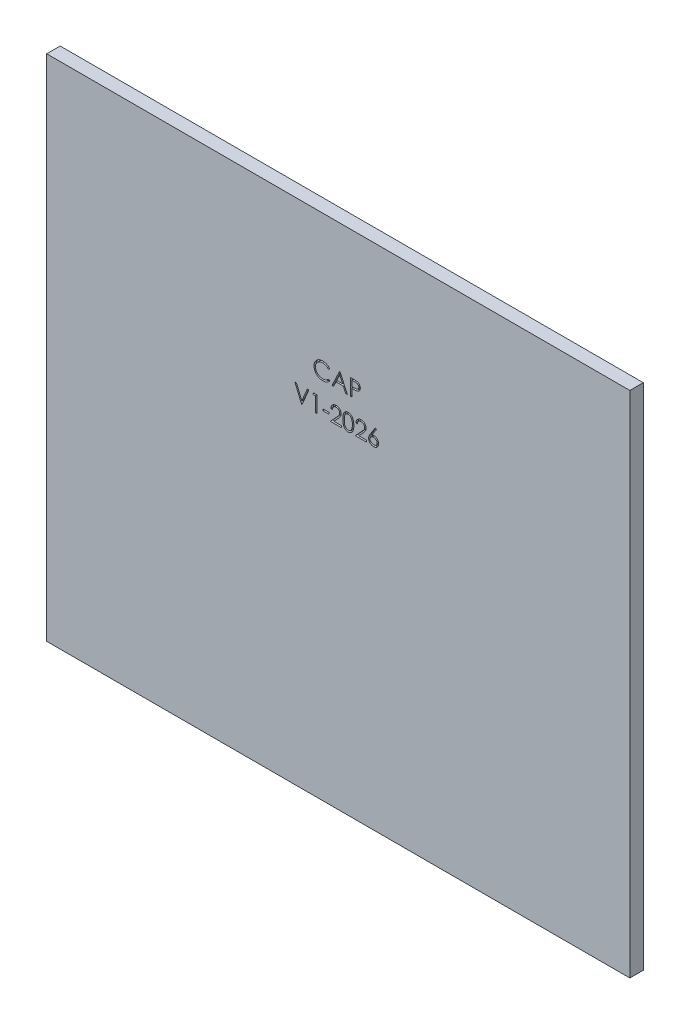
SolidWorks part; units mm, degrees
ref_plane "Plan de face" through (0, 0, 0) normal (0, 0, 1) x (1, 0, 0)
ref_plane "Plan de dessus" through (0, 0, 0) normal (0, 1, 0) x (1, 0, 0)
ref_plane "Plan de droite" through (0, 0, 0) normal (1, 0, 0) x (0, 0, -1)
sketch "Esquisse1" plane through (0, 0, 0) normal (0, 0, 1) x (1, 0, 0)
  line L1 (-62.8, -54.8) -> (62.8, -54.8)
  line L2 (-62.8, -54.8) -> (-62.8, 54.8)
  line L3 (-62.8, 54.8) -> (62.8, 54.8)
  line L4 (62.8, -54.8) -> (62.8, 54.8)
  line L5 (-62.8, -54.8) -> (62.8, 54.8) construction
  line L6 (-62.8, 54.8) -> (62.8, -54.8) construction
  point P0 (0, 0)
  dimension "D1" = 125.6
  dimension "D2" = 109.6
extrude "Boss.-Extru.1" add sketch "Esquisse1" along normal blind 2.9
sketch "Esquisse6" plane through (0, 0, 2.9) normal (0, 0, 1) x (1, 0, 0)
  text T0 "   CAP\r\nV1-2026"
extrude "Enlèv. mat.-Extru.1" cut sketch "Esquisse6" against normal blind 0.5
